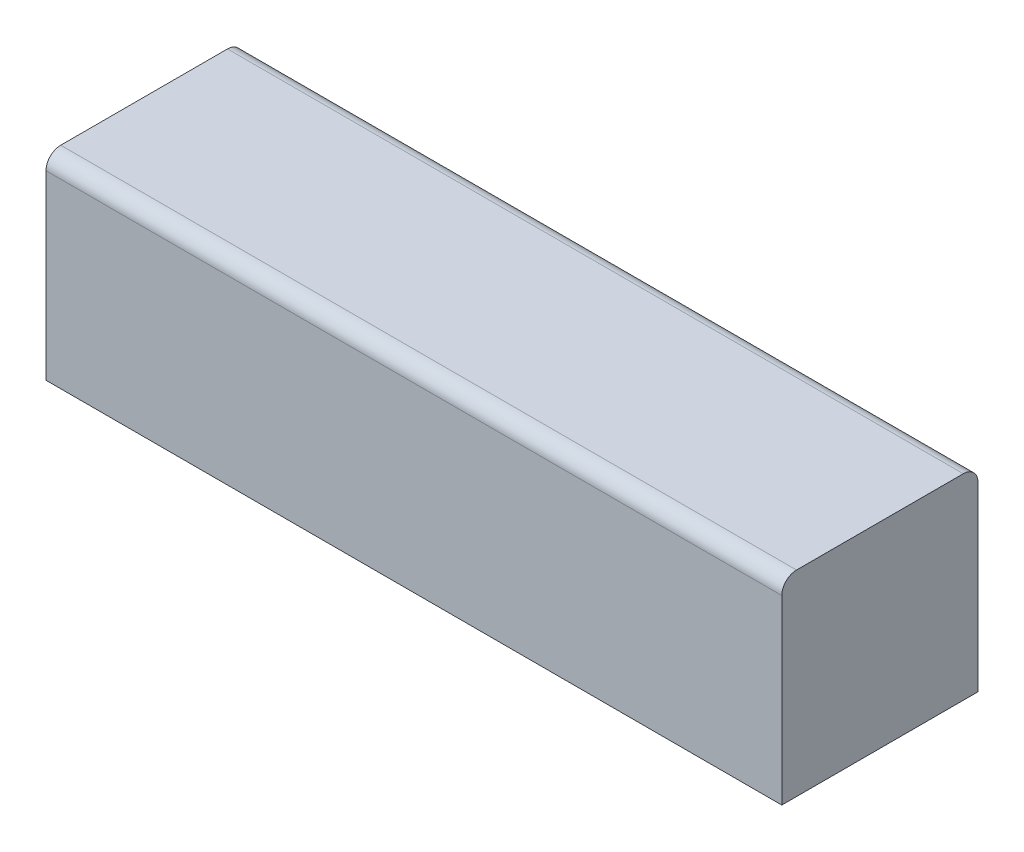
SolidWorks part; units mm, degrees
material "Aleación 1060"
ref_plane "Alzado" through (0, 0, 0) normal (0, 0, 1) x (1, 0, 0)
ref_plane "Planta" through (0, 0, 0) normal (0, 1, 0) x (1, 0, 0)
ref_plane "Vista lateral" through (0, 0, 0) normal (1, 0, 0) x (0, 0, -1)
sketch "Croquis1" plane through (0, 0, 0) normal (1, 0, 0) x (0, 0, -1)
  line L0 (-20, -10) -> (20, -10) construction
  line L1 (20, -20) -> (-20, -20)
  line L2 (20, -20) -> (20, 17)
  line L3 (17, 20) -> (-17, 20)
  line L4 (-20, -20) -> (-20, 17)
  line L5 (20, -20) -> (-20, 20) construction
  line L6 (20, 20) -> (-20, -20) construction
  arc A0 (20, 17) -> (17, 20) centre (17, 17) ccw
  arc A1 (-17, 20) -> (-20, 17) centre (-17, 17) ccw
  point P0 (0, 0)
  dimension "D3" = 3
  dimension "D1" = 40
  dimension "D2" = 40
  dimension "D4" = 10
extrude "Saliente-Extruir1" add sketch "Croquis1" along normal mid plane 150
